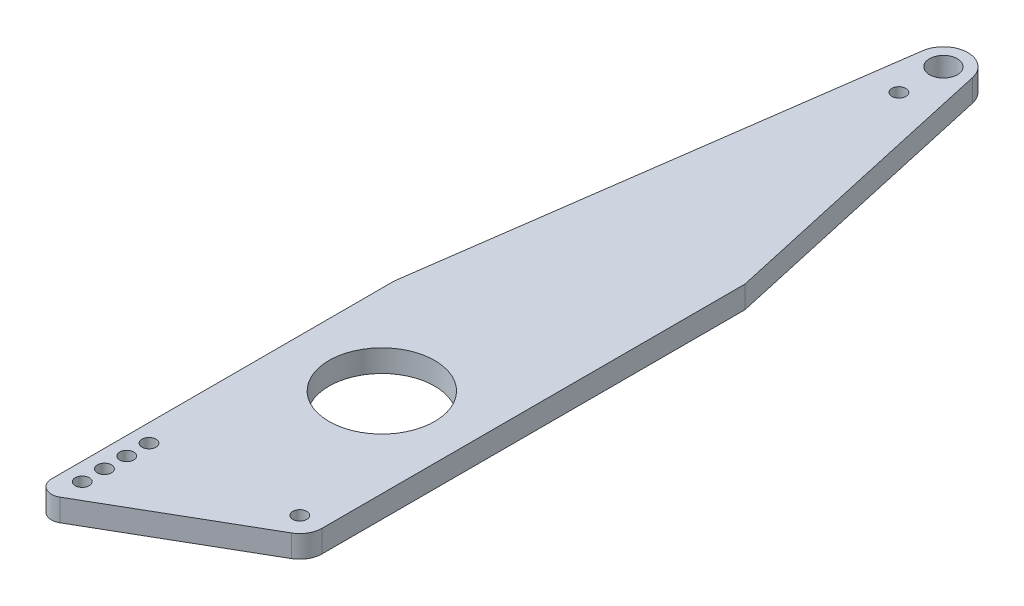
SolidWorks part; units mm, degrees
material "6061-T6 (SS)"
ref_plane "X-Y Datum" through (0, 0, 0) normal (0, 0, 1) x (1, 0, 0)
ref_plane "X-Z Datum" through (0, 0, 0) normal (0, 1, 0) x (1, 0, 0)
ref_plane "Y-Z Datum" through (0, 0, 0) normal (1, 0, 0) x (0, 0, -1)
other "Graphic1" [suppressed]
other "Graphic (Closed) -1" [suppressed]
sketch "Sketch1" plane through (0, 0, 0) normal (0, 1, 0) x (1, 0, 0)
  line L0 (25.4, -82.0382) -> (25.4, -202.7088)
  line L2 (-25.4, -229.1053) -> (-25.4, -131.2787)
  line L6 (25.4, -160.2465) -> (-25.4, -160.2465) construction
  line L28 (22.225, -208.2081) -> (-19.685, -232.4048)
  line L29 (0, 0) -> (41.91, 0) construction
  line L30 (41.91, 0) -> (0, -160.2465) construction
  line L31 (0, -160.2465) -> (0, 0) construction
  line L32 (-20.32, -219.075) -> (-20.32, -212.725) construction
  line L33 (25.4, -82.0382) -> (6.8184, 1.5163)
  line L34 (-25.4, -131.2787) -> (-6.9178, 0.9668)
  circle A0 centre (0, 0) radius 3.9688
  circle A2 centre (0, -160.2465) radius 15.0813
  circle A6 centre (-20.32, -225.425) radius 2
  circle A7 centre (-20.32, -219.075) radius 2
  circle A8 centre (-20.32, -212.725) radius 2
  circle A9 centre (-20.32, -206.375) radius 2
  arc A10 (6.8184, 1.5163) -> (-6.9178, 0.9668) centre (0, 0) ccw
  circle A41 centre (0, -12.7) radius 2
  arc A42 (-25.4, -229.1053) -> (-19.685, -232.4048) centre (-21.59, -229.1053) ccw
  arc A43 (25.4, -202.7088) -> (22.225, -208.2081) centre (19.05, -202.7088) cw
  circle A44 centre (19.05, -202.7088) radius 2
  point P21 (-20.32, -215.9)
  point P30 (25.4, -206.375)
  dimension "D1" = 7.9375
  dimension "D4" = 30.1625
  dimension "D8" = 4
  dimension "D6" = 6.985
  dimension "D65" = 4
  dimension "D18" = 3.81
  dimension "D20" = 6.35
  dimension "D22" = 4
  dimension "D9" = 5.08
  dimension "D11" = 6.35
  dimension "D12" = 6.35
  dimension "D13" = 6.35
  dimension "D5" = 50.8
  dimension "D66" = 12.7
  dimension "D2" = 41.91
  dimension "D3" = 165.6363
  dimension "D7" = 215.9
  dimension "D10" = 120
  dimension "D19" = 206.375
extrude "Boss-Extrude1" add sketch "Sketch1" against normal blind 6.35
sketch "Sketch9" plane through (0, 0, 0) normal (0, 1, 0) x (1, 0, 0)
  line L0 (0, 0) -> (0, -162.7876)
  line L1 (0, -162.7876) -> (41.91, 0)
  line L2 (41.91, 0) -> (0, 0)
  line L3 (0, 0) -> (39.3048, -10.1191) construction
  dimension "D1" = 168.096
  dimension "D2" = 0
  dimension "D3" = 41.91
  dimension "D4" = 40.5865
  dimension "D5" = 75.563
  dimension "D6" = 162.7876
sketch "Sketch4" plane through (0, 0, 0) normal (0, 1, 0) x (1, 0, 0)
  line L0 (0, -34.29) -> (0, 0)
  line L1 (0, 0) -> (152.4, 0)
  line L2 (152.4, 0) -> (0, -34.29)
  line L3 (0, 0) -> (7.3435, -32.6377) construction
  dimension "D1" = 12.68
  dimension "D2" = 156.21
  dimension "D3" = 34.29
  dimension "D4" = 152.4
  dimension "D5" = 33.4537
sketch "Sketch10" plane through (-25.4, 0, 0) normal (-1, 0, 0) x (0, 0, 1)
  line L0 (197.3553, 0) -> (197.3553, -6.35)
  line L1 (131.2787, 0) -> (229.1053, 0) construction
  line L2 (131.2787, -6.35) -> (229.1053, -6.35) construction
  line L5 (229.1053, -6.35) -> (229.1053, 0) construction
  dimension "D1" = 31.75
split line "Split Line1"
equation "\"toePadMount\"=0.25"
equation "\"D11@Sketch1\"=\"toePadMount\""
equation "\"D12@Sketch1\"=\"toePadMount\""
equation "\"D13@Sketch1\"=\"toePadMount\""
